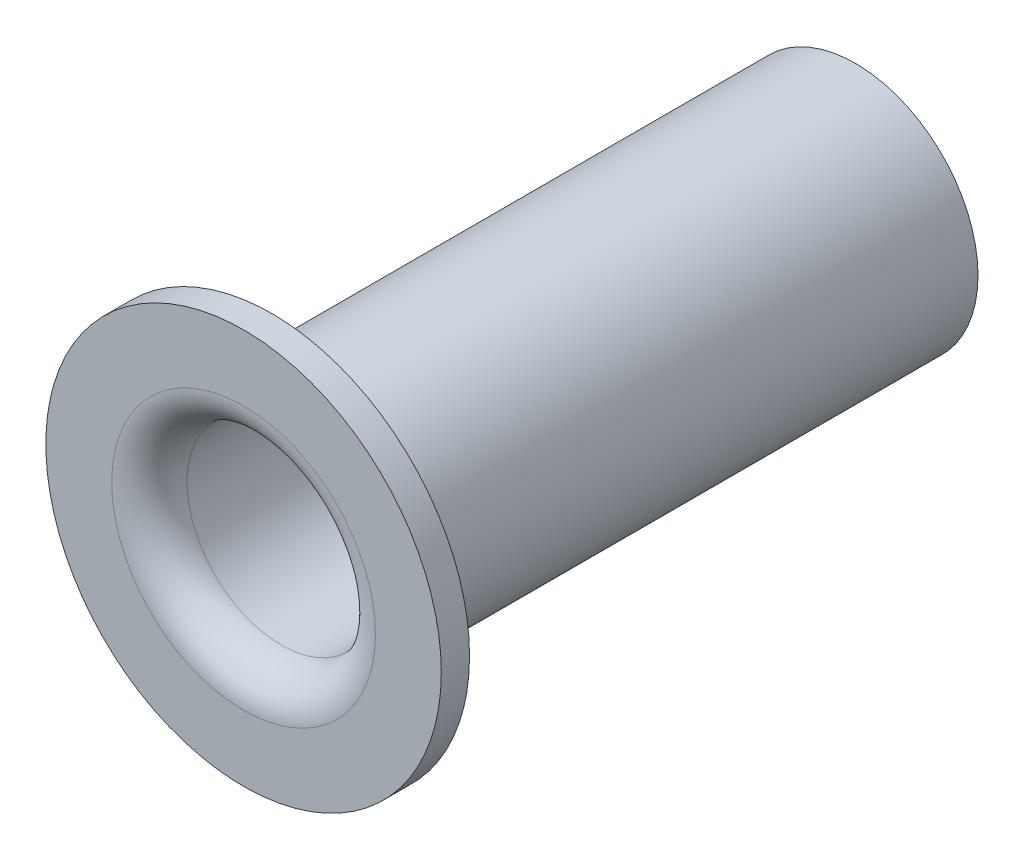
SolidWorks part; units mm, degrees
ref_plane "Plan de face" through (0, 0, 0) normal (0, 0, 1) x (1, 0, 0)
ref_plane "Plan de dessus" through (0, 0, 0) normal (0, 1, 0) x (1, 0, 0)
ref_plane "Plan de droite" through (0, 0, 0) normal (1, 0, 0) x (0, 0, -1)
sketch "Esquisse1" plane through (0, 0, 0) normal (1, 0, 0) x (0, 0, -1)
  line L0 (-0.3, 0) -> (6.2, 0) construction
  line L1 (6.2, 1) -> (6.2, 1.3)
  line L2 (6.2, 1.3) -> (0.1, 1.3)
  line L3 (0, 1.4) -> (0, 2.1)
  line L4 (0, 2.1) -> (-0.3, 2.1)
  line L5 (-0.3, 2.1) -> (-0.3, 1.4)
  line L6 (0.1, 1) -> (6.2, 1)
  arc A0 (0.1, 1.3) -> (0, 1.4) centre (0.1, 1.4) cw
  arc A1 (-0.3, 1.4) -> (0.1, 1) centre (0.1, 1.4) ccw
  point P8 (-0.3, 0)
  point P12 (6.2, 0)
  point P15 (0, 0)
  point P16 (0, 0)
  point P17 (0, 0)
  point P18 (0.2132, 1.5132)
  dimension "D1" = 2
  dimension "D7" = 0.4
  dimension "D2" = 2.6
  dimension "D4" = 6.5
  dimension "D5" = 4.2
revolve "base" add sketch "Esquisse1" angle 360 about L0
